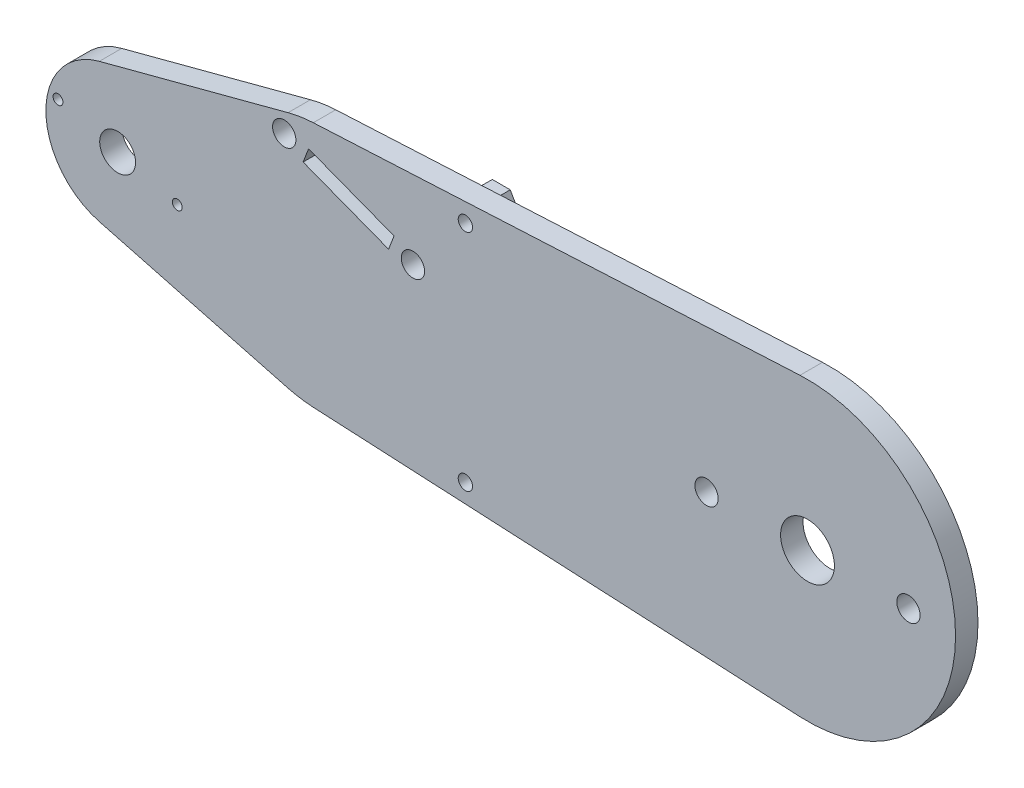
SolidWorks part; units mm, degrees
ref_plane "Front Plane" through (0, 0, 0) normal (0, 0, 1) x (1, 0, 0)
ref_plane "Top Plane" through (0, 0, 0) normal (0, 1, 0) x (1, 0, 0)
ref_plane "Right Plane" through (0, 0, 0) normal (1, 0, 0) x (0, 0, -1)
sketch "Sketch1" plane through (0, 0, 0) normal (0, 0, 1) x (1, 0, 0)
  line L0 (-51.875, 0) -> (51.875, 0) construction
  line L3 (-58.2658, 27.4648) -> (50.206, 32.9578)
  line L4 (-58.2658, -27.4648) -> (50.206, -32.9578)
  line L5 (-46.875, 0) -> (-56.875, 0) construction
  line L6 (-46.875, -18) -> (-56.875, -18) construction
  line L7 (-46.875, 18) -> (-56.875, 18) construction
  line L8 (-51.875, 0) -> (-101.875, 0) construction
  line L9 (-105.9639, 15.4687) -> (-63.9028, 26.5868)
  line L10 (-105.9639, -15.4687) -> (-63.9028, -26.5868)
  arc A3 (50.206, -32.9578) -> (50.206, 32.9578) centre (51.875, 0) ccw
  circle A5 centre (51.875, 0) radius 6
  arc A6 (-46.875, -18) -> (-46.875, 18) centre (-46.875, 0) ccw construction
  arc A7 (-56.875, 18) -> (-56.875, -18) centre (-56.875, 0) ccw construction
  arc A8 (-58.2658, 27.4648) -> (-58.2658, -27.4648) centre (-56.875, 0) ccw
  circle A9 centre (-101.875, 0) radius 4
  circle A10 centre (-101.875, 0) radius 16
  point P9 (-51.875, 0)
  dimension "D1" = 103.75
  dimension "D2" = 66
  dimension "D3" = 8
  dimension "D5" = 12
  dimension "D7" = 18
  dimension "D8" = 55
  dimension "D9" = 32
  dimension "D4" = 51.875
  dimension "D6" = 10
  dimension "D10" = 50
extrude "Boss-Extrude1" add sketch "Sketch1" along normal blind 5 contours A10 L10 A8 L9 | A10 A9 | L3 A8 L4 A3 A5
sketch "Sketch7" plane through (0, 0, 5) normal (0, 0, 1) x (1, 0, 0)
  line L0 (51.875, 5) -> (51.875, -5) construction
  line L1 (51.875, 0) -> (29.375, 0) construction
  circle A0 centre (51.875, 0) radius 5 construction
  circle A1 centre (29.375, 0) radius 2.6
  circle A2 centre (74.375, 0) radius 2.6
  dimension "D1" = 5.2
  dimension "D2" = 22.5
extrude "Cut-Extrude1" cut sketch "Sketch7" against normal blind 7
sketch "Sketch8" plane through (0, 0, 5) normal (0, 0, 1) x (1, 0, 0)
  line L0 (-84.375, 0) -> (-24.375, 0) construction
  line L1 (-24.375, 0) -> (-24.375, 25) construction
  line L3 (-26.375, 28.4641) -> (-28.375, 25)
  line L4 (-28.375, 25) -> (-26.375, 21.5359)
  line L5 (-26.375, 21.5359) -> (-22.375, 21.5359)
  line L6 (-22.375, 21.5359) -> (-20.375, 25)
  line L7 (-20.375, 25) -> (-22.375, 28.4641)
  line L8 (-22.375, 28.4641) -> (-26.375, 28.4641)
  line L9 (-25.9916, 27.8) -> (-27.6082, 25)
  line L10 (-27.6082, 25) -> (-25.9916, 22.2)
  line L11 (-25.9916, 22.2) -> (-22.7584, 22.2)
  line L12 (-22.7584, 22.2) -> (-21.1418, 25)
  line L13 (-21.1418, 25) -> (-22.7584, 27.8)
  line L14 (-22.7584, 27.8) -> (-25.9916, 27.8)
  arc A0 (-58.2658, 27.4648) -> (-58.2658, -27.4648) centre (-56.875, 0) ccw construction
  circle A1 centre (-24.375, 25) radius 3.4641 construction
  circle A2 centre (-24.375, 25) radius 2.8 construction
  dimension "D1" = 8
  dimension "D2" = 5.6
  dimension "D3" = 25
  dimension "D4" = 60
extrude "Boss-Extrude6" add sketch "Sketch8" against normal blind 8
sketch "Sketch9" plane through (0, 0, 5) normal (0, 0, 1) x (1, 0, 0)
  line L0 (-24.375, 27.4682) -> (-24.375, 22.5318) construction
  line L1 (-22.95, 27.4682) -> (-25.8, 27.4682) construction
  line L2 (-25.8, 22.5318) -> (-22.95, 22.5318) construction
  circle A0 centre (-24.375, 25) radius 1.6
  dimension "D1" = 3.2
extrude "Cut-Extrude2" cut sketch "Sketch9" against normal blind 6
mirror "Mirror1" about plane through (0, 0, 0) normal (0, 1, 0) of "Boss-Extrude6"
mirror "Mirror2" about plane through (0, 0, 0) normal (0, 1, 0) of "Cut-Extrude2"
sketch "Sketch10" plane through (0, 0, 5) normal (0, 0, 1) x (1, 0, 0)
  line L0 (51.875, 0) -> (-101.875, 0) construction
  line L1 (-41.6054, 11.695) -> (-60.2795, 18.8558)
  line L2 (-60.2795, 18.8558) -> (-59.2054, 21.657)
  line L3 (-59.2054, 21.657) -> (-40.5313, 14.4961)
  line L4 (-40.5313, 14.4961) -> (-41.6054, 11.695)
  line L5 (-50.9424, 15.2754) -> (-49.8683, 18.0765) construction
  line L6 (-50.9424, 15.2754) -> (-56.8, 0) construction
  line L7 (-41.6054, 11.695) -> (-46.09, 0) construction
  line L8 (-60.2795, 18.8558) -> (-67.6186, 0) construction
  line L9 (-25, 0) -> (-81.9162, 21.8253) construction
  line L10 (-41.0683, 13.0956) -> (-36.0683, 11.1782) construction
  line L11 (-105.9639, 15.4687) -> (-63.9028, 26.5868) construction
  circle A0 centre (-36.0683, 11.1782) radius 2.6
  circle A1 centre (-64.7424, 22.1737) radius 2.6
  point P10 (-25, 0)
  dimension "D7" = 5.2
  dimension "D1" = 31.8
  dimension "D2" = 20
  dimension "D3" = 3
  dimension "D4" = 16.36
  dimension "D5" = 34.2564
  dimension "D6" = 20.98
  dimension "D8" = 5
extrude "Boss-Extrude7" add sketch "Sketch10" along normal blind 5
sketch "Sketch12" plane through (0, 0, 10) normal (0, 0, 1) x (1, 0, 0)
  line L0 (-59.2054, 21.657) -> (-41.6054, 11.695) construction
  line L1 (-59.3205, 21.9153) -> (-40.2729, 14.6112)
  line L2 (-40.2729, 14.6112) -> (-41.4902, 11.4367)
  line L3 (-41.4902, 11.4367) -> (-60.5378, 18.7407)
  line L4 (-60.5378, 18.7407) -> (-59.3205, 21.9153)
  line L5 (-40.5313, 14.4961) -> (-59.2054, 21.657) construction
  line L6 (-59.2054, 21.657) -> (-60.2795, 18.8558) construction
  line L7 (-60.2795, 18.8558) -> (-41.6054, 11.695) construction
  line L8 (-41.6054, 11.695) -> (-40.5313, 14.4961) construction
  line L9 (-50.4054, 16.676) -> (-49.7967, 18.2633) construction
  line L10 (-41.6054, 11.695) -> (-40.5313, 14.4961) construction
  circle A0 centre (-36.0683, 11.1782) radius 2.6
  circle A1 centre (-64.7424, 22.1737) radius 2.6
  dimension "D1" = 0.2
  dimension "D2" = 0.2
  dimension "D3" = 0.2
  dimension "D4" = 0.2
extrude "Cut-Extrude4" cut sketch "Sketch12" against normal blind 10
sketch "Sketch11" plane through (0, 0, 5) normal (0, 0, 1) x (1, 0, 0)
  line L0 (-105.9639, -15.4687) -> (-101.875, 0) construction
  line L1 (-88.5816, -3.5139) -> (-101.875, 0) construction
  circle A0 centre (-101.875, 0) radius 13.75 construction
  circle A3 centre (-88.5816, -3.5139) radius 1.1
  circle A4 centre (-115.1684, 3.5139) radius 1.1
  dimension "D2" = 2.2
  dimension "D3" = 27.5
  dimension "D1" = 90
extrude "Cut-Extrude3" cut sketch "Sketch11" against normal blind 6
